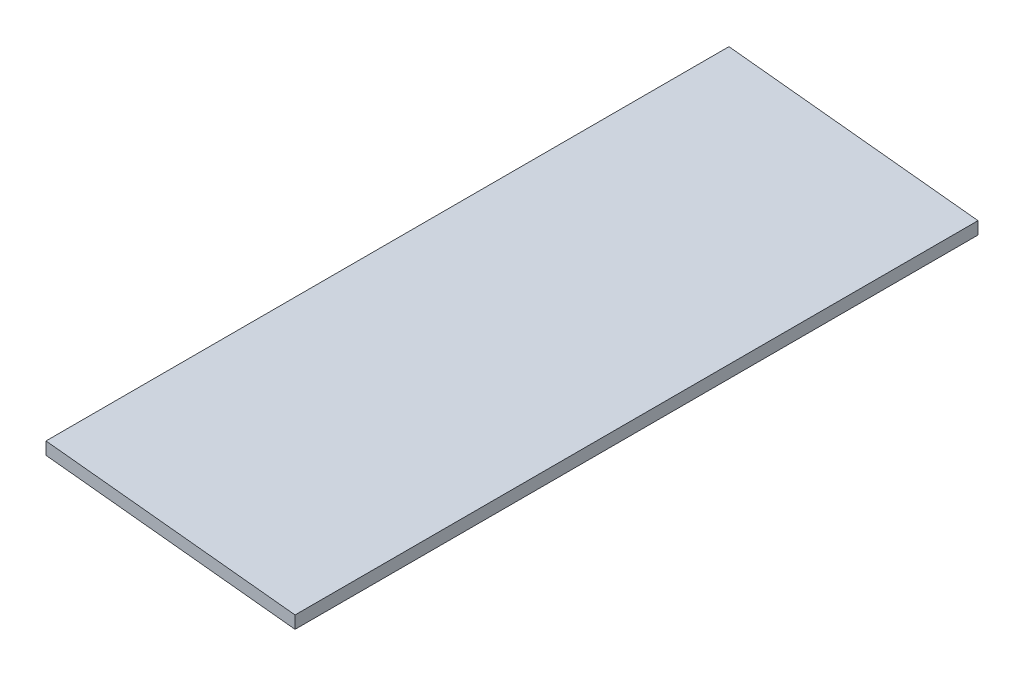
SolidWorks part; units mm, degrees
ref_plane "Front Plane" through (0, 0, 0) normal (0, 0, 1) x (1, 0, 0)
ref_plane "Top Plane" through (0, 0, 0) normal (0, 1, 0) x (1, 0, 0)
ref_plane "Right Plane" through (0, 0, 0) normal (1, 0, 0) x (0, 0, -1)
sketch "Sketch2" plane through (0, 0, 0) normal (0, 0, 1) x (1, 0, 0)
  line L0 (0, 0) -> (0, 6.033)
  line L1 (0, 6.033) -> (120.3371, -6.6149)
  line L2 (120.3371, -6.6149) -> (120.3371, -12.6479)
  line L3 (120.3371, -12.6479) -> (0, 0)
  line L4 (120.3371, -12.6479) -> (0, -12.6479) construction
  point P6 (0, 0)
  point P7 (148.6024, -15.6187)
  dimension "D1" = 6
  dimension "D2" = 121
  dimension "D3" = 6
extrude "Boss-Extrude2" add sketch "Sketch2" along normal mid plane 330
